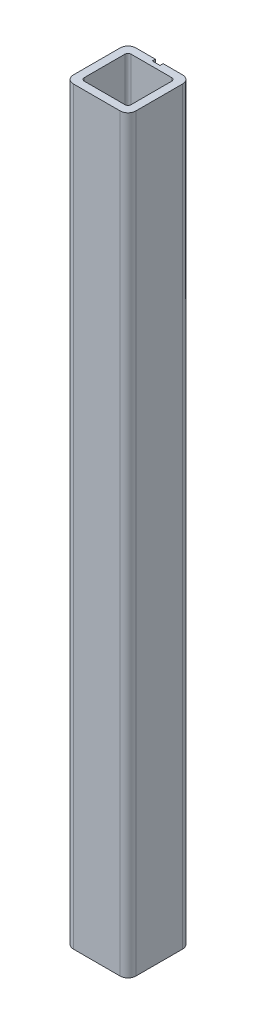
SolidWorks part; units mm, degrees
ref_plane "Front Plane" through (0, 0, 0) normal (0, 0, 1) x (1, 0, 0)
ref_plane "Top Plane" through (0, 0, 0) normal (0, 1, 0) x (1, 0, 0)
ref_plane "Right Plane" through (0, 0, 0) normal (1, 0, 0) x (0, 0, -1)
sketch "Sketch1" plane through (0, 0, 0) normal (0, 1, 0) x (1, 0, 0)
  line L1 (0, 0) -> (50.8, 0)
  line L2 (0, 0) -> (0, 50.8)
  line L3 (0, 50.8) -> (50.8, 50.8)
  line L4 (50.8, 0) -> (50.8, 50.8)
  dimension "D1" = 50.8
  dimension "D2" = 50.8
extrude "Boss-Extrude1" add sketch "Sketch1" along normal blind 558.8
sketch "Sketch3" plane through (0, 0, 0) normal (0, -1, 0) x (1, 0, 0)
  line L1 (0, -50.8) -> (50.8, -50.8)
  line L2 (0, -50.8) -> (0, 0)
  line L3 (0, 0) -> (50.8, 0)
  line L4 (50.8, -50.8) -> (50.8, 0)
extrude "Boss-Extrude2" add sketch "Sketch3" along normal blind 50.8
fillet "Fillet2" radius 6.35 4 edges at (0, 254, -50.8) (50.8, 254, -50.8) (50.8, 254, 0) (0, 254, 0)
sketch "Sketch4" plane through (0, 0, -50.8) normal (0, 0, -1) x (-1, 0, 0)
  line L0 (-44.45, 558.8) -> (-6.35, 558.8) construction
  line L1 (-22.225, 558.8) -> (-28.575, 558.8)
  line L2 (-22.225, 558.8) -> (-22.225, -50.8)
  line L3 (-22.225, -50.8) -> (-28.575, -50.8)
  line L4 (-28.575, 558.8) -> (-28.575, -50.8)
  line L5 (-6.35, -50.8) -> (-44.45, -50.8) construction
  line L6 (-22.225, 558.8) -> (-6.35, 558.8) construction
  line L7 (-28.575, 558.8) -> (-44.45, 558.8) construction
  dimension "D1" = 6.35
extrude "Cut-Extrude2" cut sketch "Sketch4" against normal blind 2.54
sketch "Sketch5" plane through (0, 558.8, 0) normal (0, 1, 0) x (1, 0, 0)
  line L8 (28.575, 48.26) -> (22.225, 48.26)
  line L9 (22.225, 48.26) -> (22.225, 50.8)
  line L10 (22.225, 50.8) -> (6.35, 50.8)
  line L11 (0, 44.45) -> (0, 6.35)
  line L12 (6.35, 0) -> (44.45, 0)
  line L13 (50.8, 6.35) -> (50.8, 44.45)
  line L14 (44.45, 50.8) -> (28.575, 50.8)
  line L15 (28.575, 50.8) -> (28.575, 48.26)
  line L16 (28.575, 48.26) -> (22.225, 48.26)
  line L17 (22.225, 48.26) -> (22.225, 50.8)
  line L18 (22.225, 50.8) -> (6.35, 50.8)
  line L19 (0, 44.45) -> (0, 6.35)
  line L20 (6.35, 0) -> (44.45, 0)
  line L21 (50.8, 6.35) -> (50.8, 44.45)
  line L22 (44.45, 50.8) -> (28.575, 50.8)
  line L23 (28.575, 50.8) -> (28.575, 48.26)
  line L24 (34.925, 44.45) -> (15.875, 44.45)
  line L32 (34.925, 41.91) -> (15.875, 41.91)
  line L33 (15.875, 41.91) -> (15.875, 44.45)
  line L34 (15.875, 44.45) -> (6.35, 44.45)
  line L35 (6.35, 44.45) -> (6.35, 6.35)
  line L36 (6.35, 6.35) -> (44.45, 6.35)
  line L37 (44.45, 6.35) -> (44.45, 44.45)
  line L38 (44.45, 44.45) -> (34.925, 44.45)
  line L39 (34.925, 44.45) -> (34.925, 41.91)
  line L42 (15.875, 44.45) -> (8.89, 44.45)
  line L43 (6.35, 41.91) -> (6.35, 8.89)
  line L44 (8.89, 6.35) -> (41.91, 6.35)
  line L45 (44.45, 8.89) -> (44.45, 41.91)
  line L46 (41.91, 44.45) -> (34.925, 44.45)
  arc A0 (8.89, 44.45) -> (6.35, 41.91) centre (8.89, 41.91) ccw
  arc A1 (44.45, 41.91) -> (41.91, 44.45) centre (41.91, 41.91) ccw
  arc A2 (41.91, 6.35) -> (44.45, 8.89) centre (41.91, 8.89) ccw
  arc A3 (6.35, 8.89) -> (8.89, 6.35) centre (8.89, 8.89) ccw
  arc A4 (6.35, 50.8) -> (0, 44.45) centre (6.35, 44.45) ccw
  arc A5 (0, 6.35) -> (6.35, 0) centre (6.35, 6.35) ccw
  arc A6 (44.45, 0) -> (50.8, 6.35) centre (44.45, 6.35) ccw
  arc A7 (50.8, 44.45) -> (44.45, 50.8) centre (44.45, 44.45) ccw
  arc A8 (6.35, 50.8) -> (0, 44.45) centre (6.35, 44.45) ccw
  arc A9 (0, 6.35) -> (6.35, 0) centre (6.35, 6.35) ccw
  arc A10 (44.45, 0) -> (50.8, 6.35) centre (44.45, 6.35) ccw
  arc A11 (50.8, 44.45) -> (44.45, 50.8) centre (44.45, 44.45) ccw
  dimension "D3" = 2.54
  dimension "D1" = 0
  dimension "D2" = 6.35
extrude "Cut-Extrude3" cut sketch "Sketch5" against normal through all contours L42 A0 L43 A3 L44 A2 L45 A1 L46 L24
